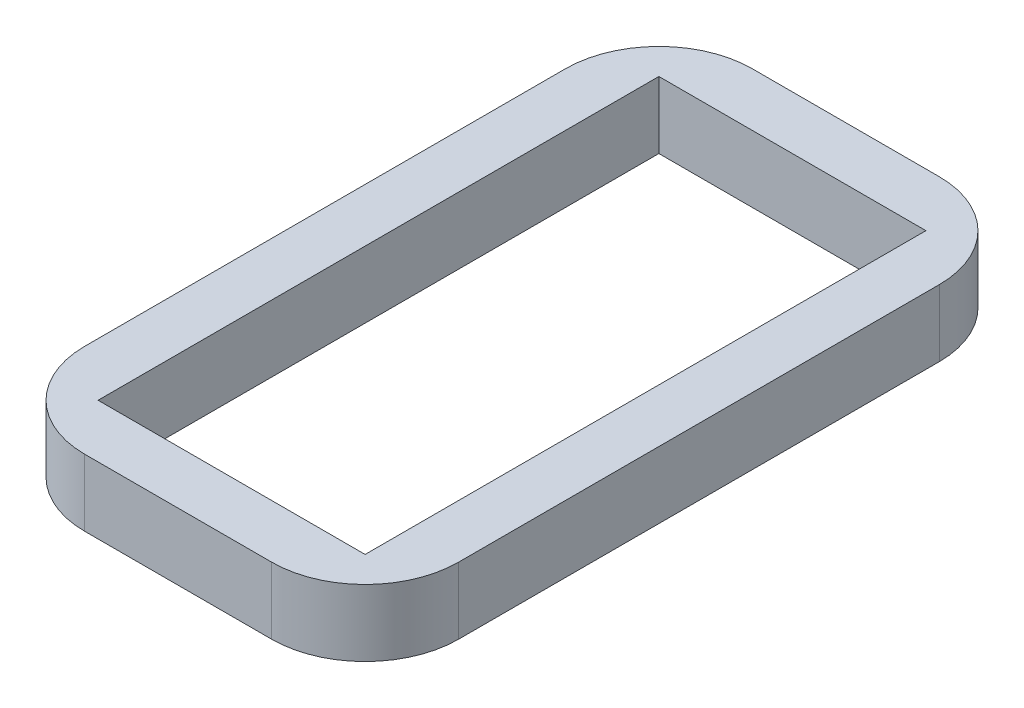
SolidWorks part; units mm, degrees
ref_plane "Plan de face" through (0, 0, 0) normal (0, 0, 1) x (1, 0, 0)
ref_plane "Plan de dessus" through (0, 0, 0) normal (0, 1, 0) x (1, 0, 0)
ref_plane "Plan de droite" through (0, 0, 0) normal (1, 0, 0) x (0, 0, -1)
sketch "Esquisse1" plane through (0, 0, 0) normal (0, 1, 0) x (1, 0, 0)
  line L1 (-10, 21) -> (10, 21)
  line L2 (-10, 21) -> (-10, -21)
  line L3 (-10, -21) -> (10, -21)
  line L4 (10, 21) -> (10, -21)
  line L5 (-10, 21) -> (10, -21) construction
  line L6 (-10, -21) -> (10, 21) construction
  line L7 (-14, 25) -> (14, 25)
  line L8 (-14, 25) -> (-14, -25)
  line L9 (-14, -25) -> (14, -25)
  line L10 (14, 25) -> (14, -25)
  line L11 (-14, 25) -> (14, -25) construction
  line L12 (-14, -25) -> (14, 25) construction
  point P0 (0, 0)
  point P5 (0, 0)
  dimension "D1" = 42
  dimension "D2" = 4
  dimension "D3" = 4
  dimension "D4" = 20
extrude "Boss.-Extru.1" add sketch "Esquisse1" along normal blind 5
fillet "Congé1" radius 7 4 edges at (-14, 2.5, -25) (14, 2.5, -25) (14, 2.5, 25) (-14, 2.5, 25)
